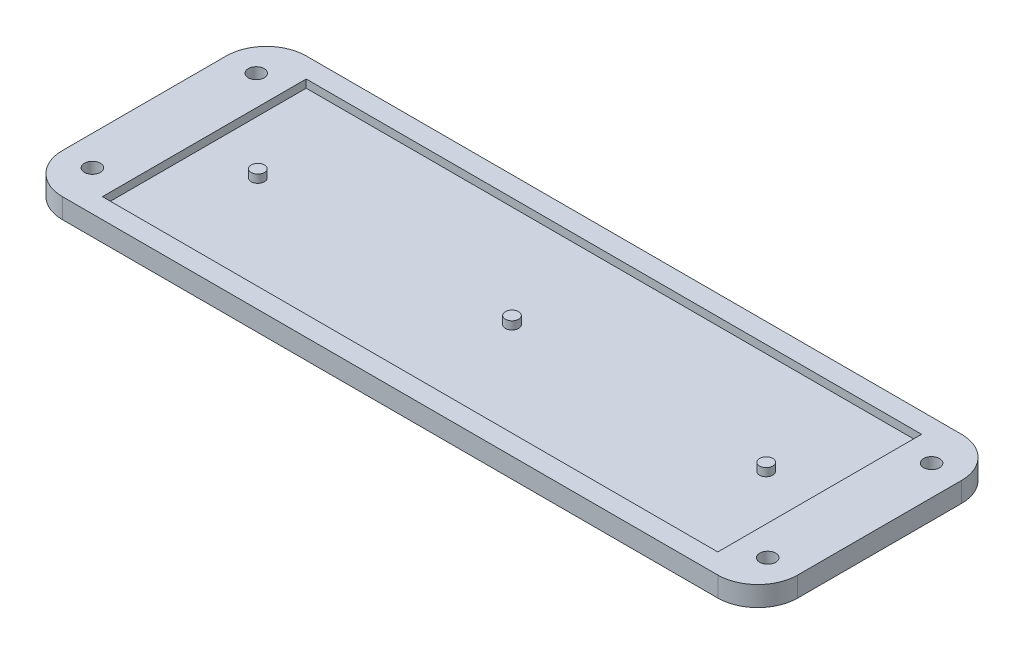
SolidWorks part; units mm, degrees
ref_plane "Front Plane" through (0, 0, 0) normal (0, 0, 1) x (1, 0, 0)
ref_plane "Top Plane" through (0, 0, 0) normal (0, 1, 0) x (1, 0, 0)
ref_plane "Right Plane" through (0, 0, 0) normal (1, 0, 0) x (0, 0, -1)
sketch "Sketch2" plane through (0, 0, 0) normal (0, 1, 0) x (1, 0, 0)
  line L0 (0, 0) -> (184, 0)
  line L1 (184, 0) -> (184, 61)
  line L2 (184, 61) -> (0, 61)
  line L3 (0, 61) -> (0, 0)
  line L4 (0, 30.5) -> (184, 30.5) construction
  line L5 (15, 56) -> (169, 56) construction
  line L6 (15, 56) -> (15, 5) construction
  line L7 (15, 5) -> (169, 5) construction
  line L8 (169, 56) -> (169, 5) construction
  line L9 (15, 56) -> (169, 5) construction
  line L10 (15, 5) -> (169, 56) construction
  line L11 (184, 30.5) -> (92, 61) construction
  line L12 (92, 61) -> (92, 0) construction
  circle A0 centre (7.5, 10) radius 2
  circle A1 centre (176.5, 10) radius 2
  circle A2 centre (176.5, 51) radius 2
  circle A3 centre (7.5, 51) radius 2
  point P3 (92, 30.5)
  dimension "D5" = 4
  dimension "D1" = 51
  dimension "D2" = 154
  dimension "D3" = 5
  dimension "D4" = 15
  dimension "D6" = 10
  dimension "D7" = 7.5
extrude "Boss-Extrude1" add sketch "Sketch2" along normal blind 5
sketch "Sketch3" plane through (0, 5, 0) normal (0, 1, 0) x (1, 0, 0)
  line L0 (0, 30.5) -> (184, 30.5) construction
  line L1 (15, 56) -> (169, 56)
  line L2 (15, 56) -> (15, 5)
  line L3 (15, 5) -> (169, 5)
  line L4 (169, 56) -> (169, 5)
  line L5 (15, 56) -> (169, 5) construction
  line L6 (15, 5) -> (169, 56) construction
  line L7 (0, 61) -> (0, 0) construction
  line L8 (184, 0) -> (184, 61) construction
  line L9 (92, 61) -> (92, 0) construction
  line L10 (184, 61) -> (0, 61) construction
  line L11 (0, 0) -> (184, 0) construction
  circle A0 centre (92, 30.5) radius 1.65
  circle A1 centre (28.4, 30.5) radius 1.65
  circle A2 centre (155.6, 30.5) radius 1.65
  point P0 (92, 30.5)
  dimension "D5" = 3.3
  dimension "D1" = 51
  dimension "D2" = 154
  dimension "D3" = 13.4
  dimension "D4" = 13.4
extrude "Cut-Extrude1" cut sketch "Sketch3" against normal blind 2
fillet "Fillet1" radius 10 4 edges at (0, 2.5, -61) (0, 2.5, 0) (184, 2.5, -61) (184, 2.5, 0)
